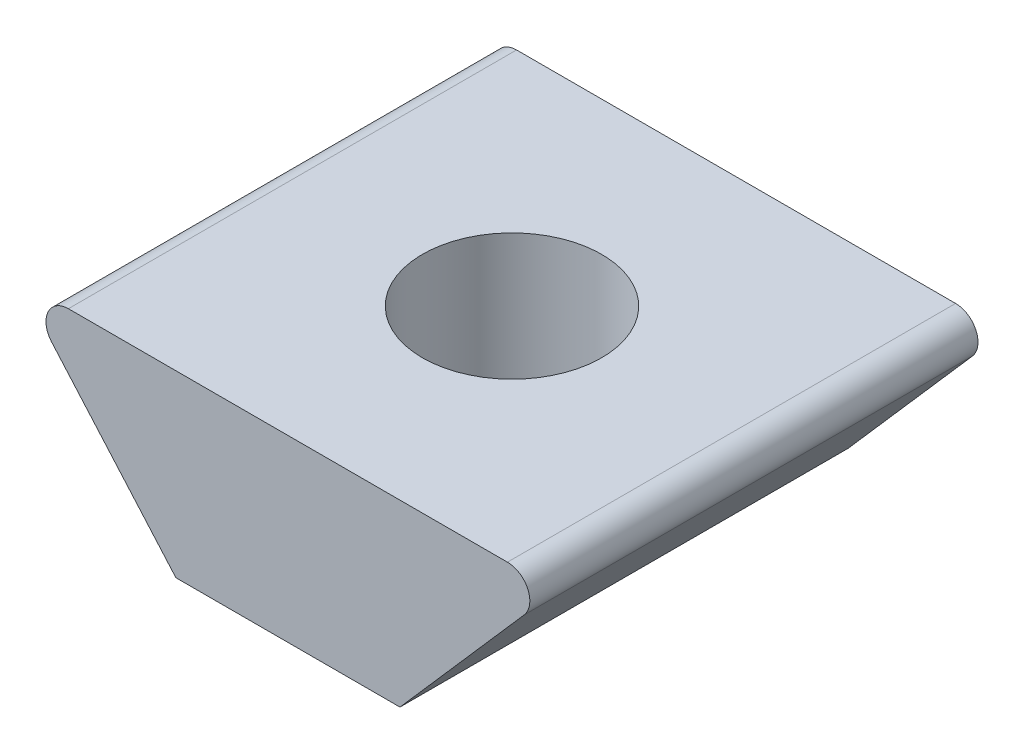
SolidWorks part; units mm, degrees
ref_plane "正面" through (0, 0, 0) normal (0, 0, 1) x (1, 0, 0)
ref_plane "平面" through (0, 0, 0) normal (0, 1, 0) x (1, 0, 0)
ref_plane "右側面" through (0, 0, 0) normal (1, 0, 0) x (0, 0, -1)
sketch "ｽｹｯﾁ2" plane through (0, 0, 0) normal (0, 0, 1) x (1, 0, 0)
  line L0 (0, 0) -> (0, 4) construction
  line L1 (-6, 4) -> (6, 4)
  line L2 (-2.5, 0) -> (2.5, 0)
  line L3 (-6, 4) -> (-2.5, 0)
  line L4 (6, 4) -> (2.5, 0)
  point P3 (0, 3.9686)
  point P6 (0, 4)
  point P9 (0, 0)
  point P10 (0, 3.3)
  dimension "D1" = 5
  dimension "D2" = 12
  dimension "D3" = 4
extrude "ﾎﾞｽ - 押し出し1" add sketch "ｽｹｯﾁ2" along normal blind 10
sketch "ｽｹｯﾁ3" plane through (0, 4, 0) normal (0, 1, 0) x (1, 0, 0)
  line L0 (0, 0) -> (0, -10) construction
  line L1 (6, -10) -> (-6, -10) construction
  circle A0 centre (0, -5) radius 2
  dimension "D1" = 4
extrude "ｶｯﾄ - 押し出し1" cut sketch "ｽｹｯﾁ3" against normal through all
fillet "ﾌｨﾚｯﾄ2" radius 0.5 2 edges at (6, 4, 5) (-6, 4, 5)
